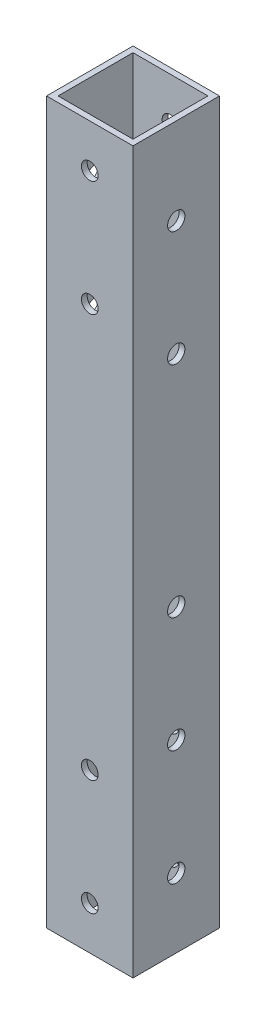
SolidWorks part; units mm, degrees
material "Thornel Mat VMA"
ref_plane "前视基准面" through (0, 0, 0) normal (0, 0, 1) x (1, 0, 0)
ref_plane "上视基准面" through (0, 0, 0) normal (0, 1, 0) x (1, 0, 0)
ref_plane "右视基准面" through (0, 0, 0) normal (1, 0, 0) x (0, 0, -1)
sketch "草图1" plane through (0, 0, 0) normal (0, 1, 0) x (1, 0, 0)
  line L1 (-7.5, -7.5) -> (7.5, -7.5)
  line L2 (-7.5, -7.5) -> (-7.5, 7.5)
  line L3 (-7.5, 7.5) -> (7.5, 7.5)
  line L4 (7.5, -7.5) -> (7.5, 7.5)
  line L5 (-7.5, -7.5) -> (7.5, 7.5) construction
  line L6 (-7.5, 7.5) -> (7.5, -7.5) construction
  point P0 (0, 0)
  dimension "D1" = 15
  dimension "D2" = 15
extrude "拉伸-薄壁1" add sketch "草图1" along normal blind 125 thin thin type one direction reverse wall 1
sketch "草图2" plane through (0, 0, 7.5) normal (0, 0, 1) x (1, 0, 0)
  line L0 (0, 0) -> (0, 125) construction
  line L1 (-7.5, 125) -> (7.5, 125) construction
  line L2 (-7.5, 0) -> (7.5, 0) construction
  line L3 (-1000, 62.5) -> (49000, 62.5) construction
  circle A0 centre (0, 7.5) radius 1.45
  circle A1 centre (0, 27.5) radius 1.45
  circle A2 centre (0, 97.5) radius 1.45
  circle A3 centre (0, 117.5) radius 1.45
  point P14 (0, 62.5)
  dimension "D1" = 2.9
  dimension "D2" = 7.5
  dimension "D3" = 20
extrude "切除-拉伸1" cut sketch "草图2" against normal through all
sketch "草图3" plane through (7.5, 0, 0) normal (1, 0, 0) x (0, 0, -1)
  line L0 (0, 0) -> (0, 125) construction
  line L1 (-7.5, 125) -> (7.5, 125) construction
  line L2 (-7.5, 0) -> (7.5, 0) construction
  circle A0 centre (0, 32) radius 1.5
  circle A1 centre (0, 12) radius 1.5
  circle A2 centre (0, 52) radius 1.5
  circle A3 centre (0, 110) radius 1.5
  circle A4 centre (0, 90) radius 1.5
  dimension "D1" = 3
  dimension "D6" = 20
  dimension "D2" = 20
  dimension "D3" = 20
  dimension "D4" = 12
  dimension "D5" = 15
extrude "切除-拉伸2" cut sketch "草图3" against normal through all
